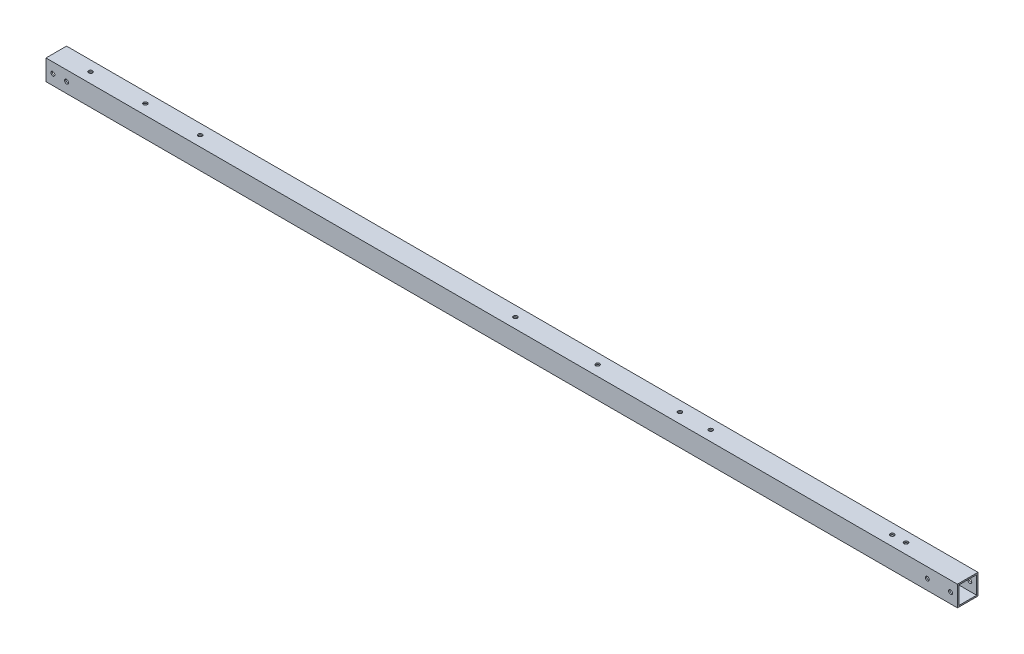
SolidWorks part; units mm, degrees
material "Thornel Mat VMA"
ref_plane "前视基准面" through (0, 0, 0) normal (0, 0, 1) x (1, 0, 0)
ref_plane "上视基准面" through (0, 0, 0) normal (0, 1, 0) x (1, 0, 0)
ref_plane "右视基准面" through (0, 0, 0) normal (1, 0, 0) x (0, 0, -1)
other "Configuration Table"
sketch "草图1" plane through (0, 0, 0) normal (1, 0, 0) x (0, 0, -1)
  line L0 (-6.5, -6.5) -> (-6.5, 6.5)
  line L1 (-7.5, -7.5) -> (7.5, -7.5)
  line L2 (-7.5, -7.5) -> (-7.5, 7.5)
  line L3 (-7.5, 7.5) -> (7.5, 7.5)
  line L4 (7.5, -7.5) -> (7.5, 7.5)
  line L5 (-7.5, -7.5) -> (7.5, 7.5) construction
  line L6 (-7.5, 7.5) -> (7.5, -7.5) construction
  line L7 (-6.5, 6.5) -> (6.5, 6.5)
  line L8 (6.5, -6.5) -> (6.5, 6.5)
  line L9 (-6.5, -6.5) -> (6.5, -6.5)
  point P0 (0, 0)
  dimension "D1" = 15
  dimension "D2" = 15
  dimension "D3" = 1
extrude "凸台-拉伸1" add sketch "草图1" along normal blind 665
sketch "草图2" plane through (0, 7.5, 0) normal (0, 1, 0) x (1, 0, 0)
  circle A0 centre (610, 0) radius 1.45 construction
  circle A1 centre (477.5, 0) radius 1.45 construction
  circle A2 centre (455, 0) radius 1.45 construction
  circle A3 centre (395, 0) radius 1.45 construction
  circle A4 centre (335, 0) radius 1.45 construction
  circle A5 centre (105, 0) radius 1.45 construction
  circle A6 centre (65, 0) radius 1.45 construction
  circle A7 centre (25, 0) radius 1.45 construction
  circle A8 centre (610, 0) radius 1.45
  circle A9 centre (477.5, 0) radius 1.45
  circle A10 centre (455, 0) radius 1.45
  circle A11 centre (395, 0) radius 1.45
  circle A12 centre (335, 0) radius 1.45
  circle A13 centre (105, 0) radius 1.45
  circle A14 centre (65, 0) radius 1.45
  circle A15 centre (25, 0) radius 1.45
  circle A16 centre (620, 0) radius 1.45 construction
  circle A17 centre (620, 0) radius 1.45
extrude "切除-拉伸1" cut sketch "草图2" against normal through all
sketch "草图3" plane through (0, 0, 7.5) normal (0, 0, 1) x (1, 0, 0)
  circle A0 centre (15, 0) radius 1.45 construction
  circle A1 centre (5, 0) radius 1.45 construction
  circle A2 centre (660, 0) radius 1.45 construction
  circle A3 centre (643, 0) radius 1.45 construction
  circle A4 centre (15, 0) radius 1.45
  circle A5 centre (5, 0) radius 1.45
  circle A6 centre (660, 0) radius 1.45
  circle A7 centre (643, 0) radius 1.45
extrude "切除-拉伸2" cut sketch "草图3" against normal through all
